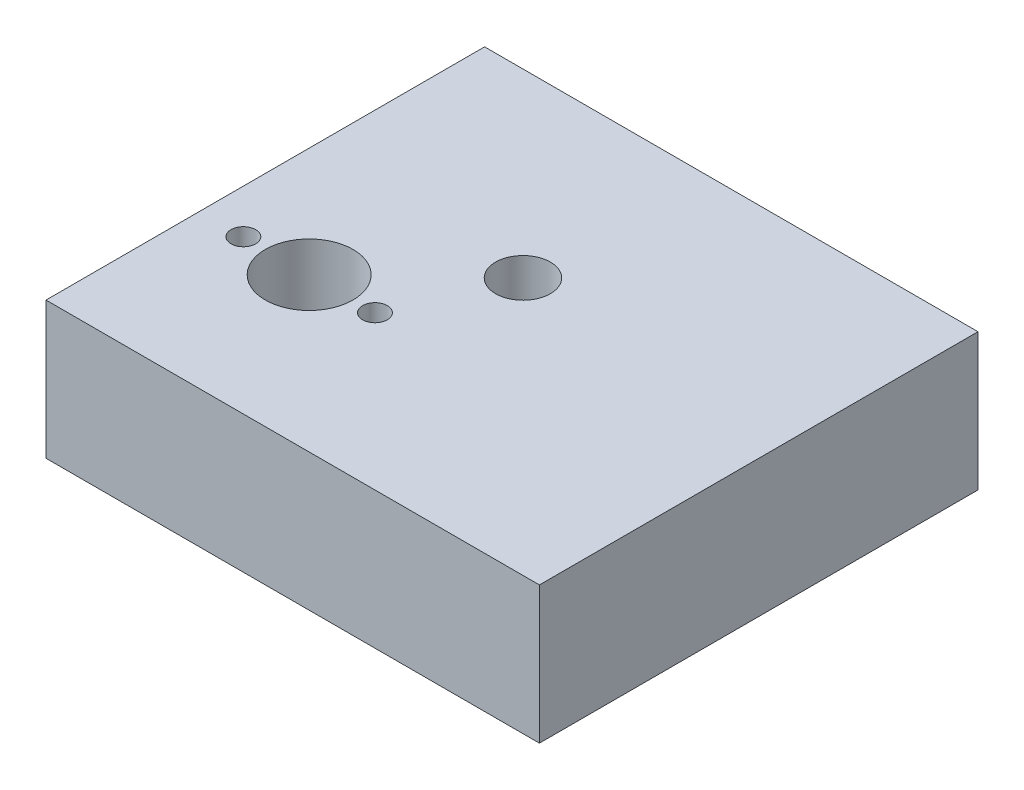
SolidWorks part; units mm, degrees
ref_plane "Front Plane" through (0, 0, 0) normal (0, 0, 1) x (1, 0, 0)
ref_plane "Top Plane" through (0, 0, 0) normal (0, 1, 0) x (1, 0, 0)
ref_plane "Right Plane" through (0, 0, 0) normal (1, 0, 0) x (0, 0, -1)
sketch "Sketch1" plane through (0, 0, 0) normal (0, 0, 1) x (1, 0, 0)
  line L1 (-45.1303, 23.1413) -> (44.8697, 23.1413)
  line L2 (-45.1303, 23.1413) -> (-45.1303, -1.8587)
  line L3 (-45.1303, -1.8587) -> (44.8697, -1.8587)
  line L4 (44.8697, 23.1413) -> (44.8697, -1.8587)
  dimension "D1" = 90
  dimension "D2" = 25
extrude "Boss-Extrude1" add sketch "Sketch1" along normal blind 80
sketch "Эскиз1" plane through (0, -1.8587, 0) normal (0, -1, 0) x (1, 0, 0)
  line L0 (-45.1303, 80) -> (-45.1303, 0) construction
  line L1 (-45.1303, 0) -> (44.8697, 0) construction
  circle A0 centre (-5.1303, 33) radius 25
  dimension "D3" = 50
  dimension "D1" = 40
  dimension "D2" = 33
extrude "Вырез-Вытянуть1" cut sketch "Эскиз1" against normal blind 10.5
sketch "Эскиз2" plane through (0, 8.6413, 0) normal (0, -1, 0) x (1, 0, 0)
  circle A0 centre (-5.1303, 33) radius 5
  circle A1 centre (-5.1303, 33) radius 25 construction
extrude "Вырез-Вытянуть2" cut sketch "Эскиз2" against normal blind 100
sketch "Эскиз3" plane through (0, -1.8587, 0) normal (0, -1, 0) x (1, 0, 0)
  line L0 (-45.1303, 80) -> (-45.1303, 0) construction
  line L1 (-45.1303, 80) -> (44.8697, 80) construction
  circle A0 centre (-25.1303, 52) radius 8
  dimension "D3" = 16
  dimension "D1" = 20
  dimension "D2" = 28
extrude "Вырез-Вытянуть3" cut sketch "Эскиз3" against normal blind 100
sketch "Эскиз4" plane through (0, -1.8587, 0) normal (0, -1, 0) x (1, 0, 0)
  circle A0 centre (-25.1303, 52) radius 10
extrude "Вырез-Вытянуть4" cut sketch "Эскиз4" against normal blind 10.5
sketch "Эскиз5" plane through (0, 23.1413, 0) normal (0, 1, 0) x (1, 0, 0)
  line L1 (44.8697, -80) -> (-45.1303, -80) construction
  circle A0 centre (-37.1303, -52) radius 2.25
  circle A1 centre (-25.1303, -52) radius 8 construction
  dimension "D1" = 12
  dimension "D2" = 28
  dimension "D3" = 4.5
extrude "Вырез-Вытянуть5" cut sketch "Эскиз5" against normal blind 10.5
pattern_linear "Линейный массив1" count 2 spacing 24 along (1, 0, 0) of "Вырез-Вытянуть5"
